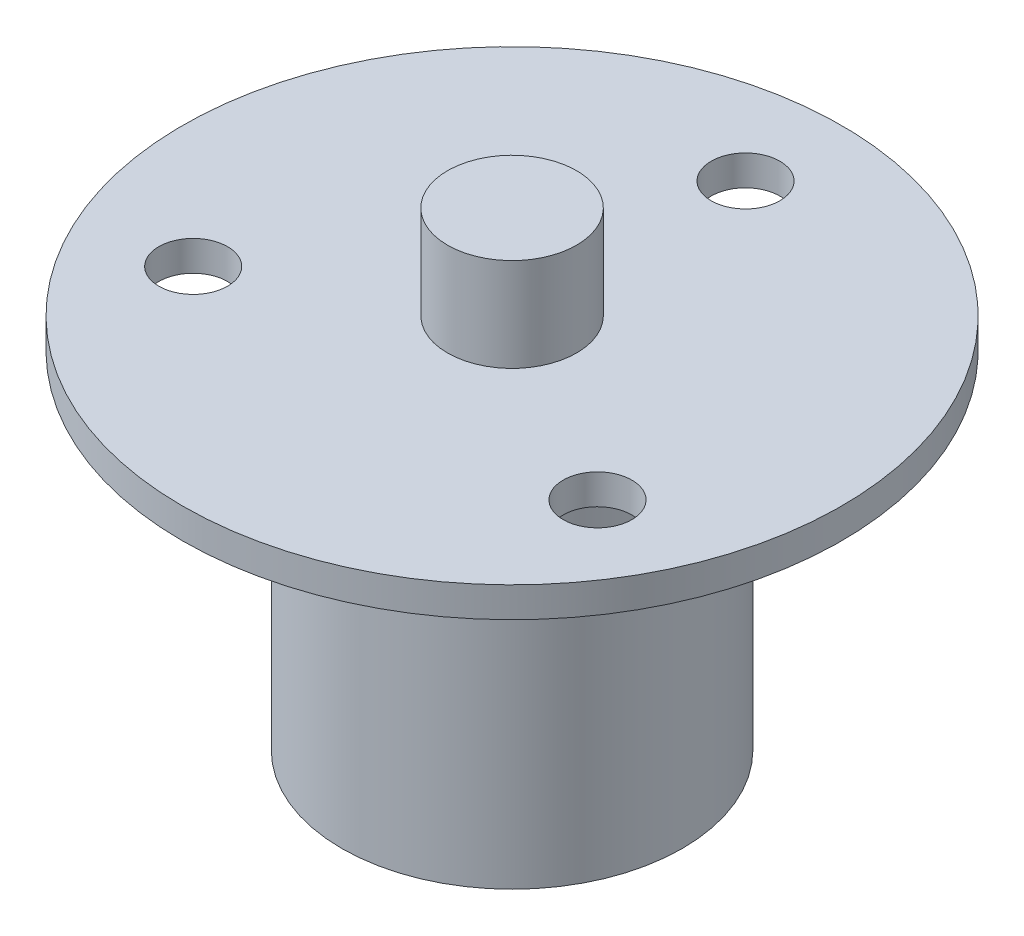
SolidWorks part; units mm, degrees
ref_plane "Front Plane" through (0, 0, 0) normal (0, 0, 1) x (1, 0, 0)
ref_plane "Top Plane" through (0, 0, 0) normal (0, 1, 0) x (1, 0, 0)
ref_plane "Right Plane" through (0, 0, 0) normal (1, 0, 0) x (0, 0, -1)
sketch "Sketch1" plane through (0, 0, 0) normal (0, 0, 1) x (1, 0, 0)
  line L0 (0, 0) -> (-6.2, 0)
  line L1 (-6.2, 0) -> (-6.2, 12.6)
  line L2 (-6.2, 12.6) -> (-12, 12.6)
  line L3 (-12, 12.6) -> (-12, 13.7)
  line L4 (-12, 13.7) -> (-2.35, 13.7)
  line L5 (-2.35, 13.7) -> (-2.35, 17.1)
  line L6 (-2.35, 17.1) -> (0, 17.1)
  line L7 (0, 17.1) -> (0, 0) construction
  line L8 (0, 0) -> (0, 17.1)
  dimension "D1" = 13.7
  dimension "D2" = 1.1
  dimension "D3" = 12.4
  dimension "D4" = 4.7
  dimension "D5" = 24
  dimension "D6" = 3.4
revolve "Revolve1" add sketch "Sketch1" angle 360 about L7
sketch "Sketch2" plane through (0, 13.7, 0) normal (0, 1, 0) x (1, 0, 0)
  line L0 (0, 0) -> (0, 12) construction
  circle A0 centre (0, 0) radius 12 construction
  circle A1 centre (0, 8.5) radius 1.25
  circle A2 centre (7.3612, -4.25) radius 1.25
  circle A3 centre (-7.3612, -4.25) radius 1.25
  point P14 (0, 0)
  dimension "D1" = 2.5
  dimension "D2" = 8.5
  dimension "D3" = 3
extrude "Cut-Extrude1" cut sketch "Sketch2" against normal up to next
